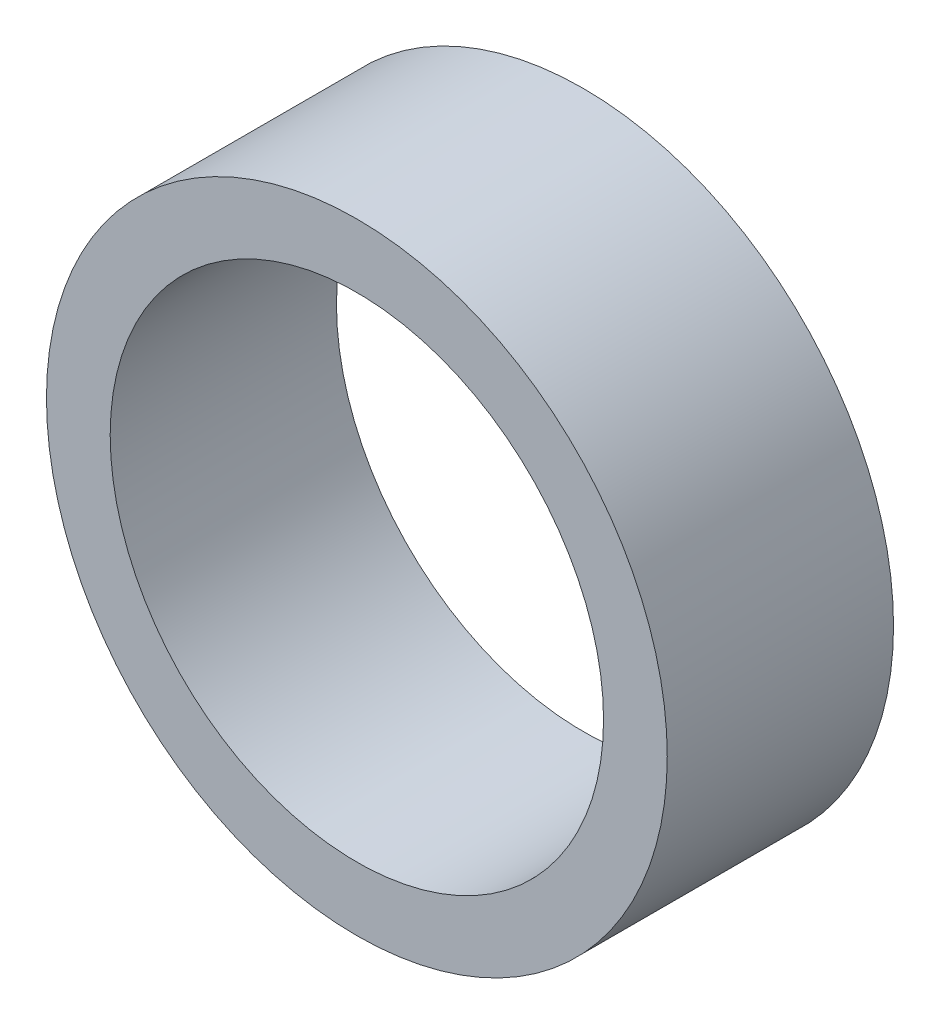
SolidWorks part; units mm, degrees
ref_plane "Front Plane" through (0, 0, 0) normal (0, 0, 1) x (1, 0, 0)
ref_plane "Top Plane" through (0, 0, 0) normal (0, 1, 0) x (1, 0, 0)
ref_plane "Right Plane" through (0, 0, 0) normal (1, 0, 0) x (0, 0, -1)
sketch "Sketch1" plane through (0, 0, 0) normal (0, 0, 1) x (1, 0, 0)
  circle A0 centre (0, 0) radius 15.1
  circle A1 centre (0, 0) radius 19
  dimension "D1" = 30.2
  dimension "D2" = 38
extrude "Boss-Extrude1" add sketch "Sketch1" along normal mid plane 13.85 contours A0 | A1
